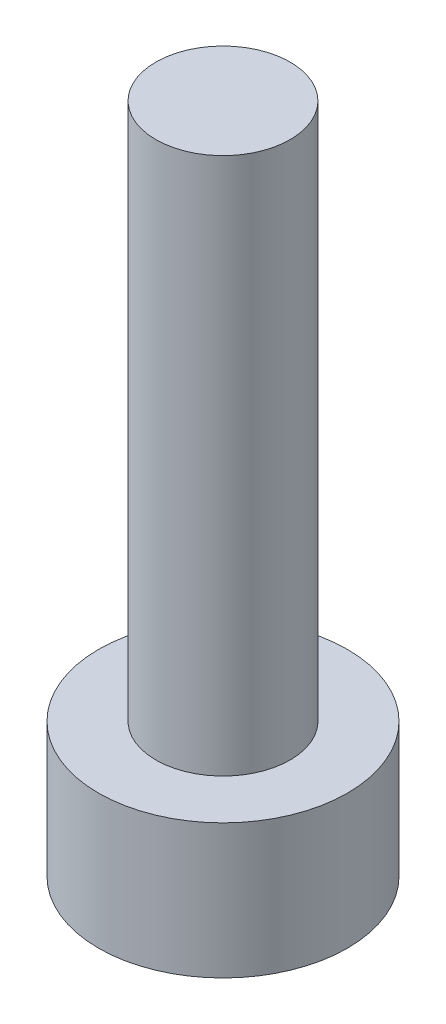
SolidWorks part; units mm, degrees
ref_plane "Front Plane" through (0, 0, 0) normal (0, 0, 1) x (1, 0, 0)
ref_plane "Top Plane" through (0, 0, 0) normal (0, 1, 0) x (1, 0, 0)
ref_plane "Right Plane" through (0, 0, 0) normal (1, 0, 0) x (0, 0, -1)
sketch "Sketch1" plane through (0, 0, 0) normal (0, 1, 0) x (1, 0, 0)
  circle A0 centre (0, 0) radius 2.78
  dimension "D1" = 5.56
extrude "Boss-Extrude1" add sketch "Sketch1" along normal blind 3
sketch "Sketch2" plane through (0, 3, 0) normal (0, 1, 0) x (1, 0, 0)
  circle A0 centre (0, 0) radius 1.5
  dimension "D1" = 3
extrude "Boss-Extrude2" add sketch "Sketch2" along normal blind 12
